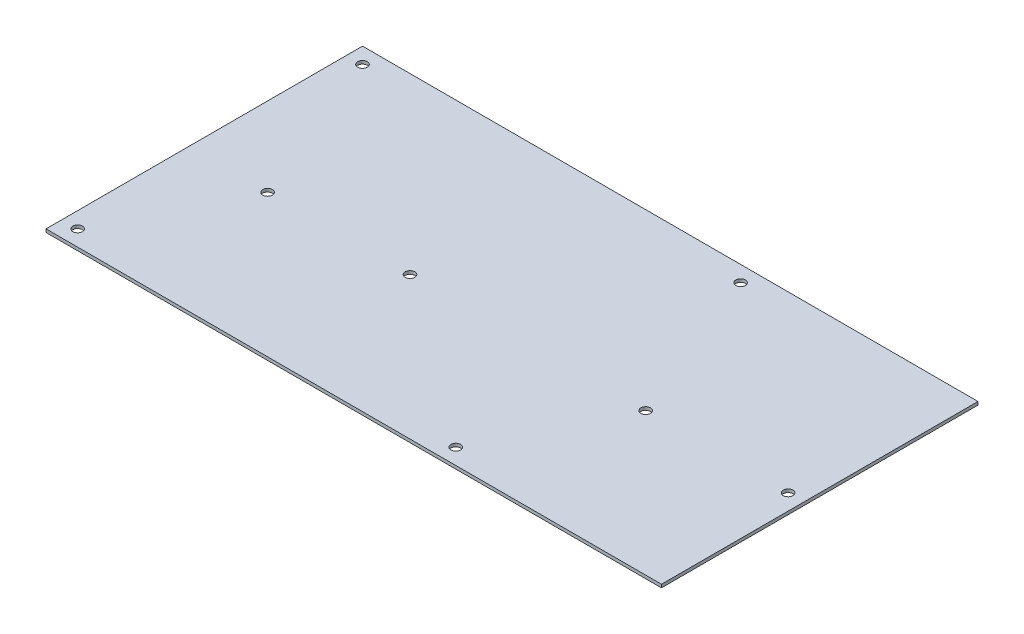
SolidWorks part; units mm, degrees
ref_plane "Front Plane" through (0, 0, 0) normal (0, 0, 1) x (1, 0, 0)
ref_plane "Top Plane" through (0, 0, 0) normal (0, 1, 0) x (1, 0, 0)
ref_plane "Right Plane" through (0, 0, 0) normal (1, 0, 0) x (0, 0, -1)
sketch "Sketch1" plane through (0, 0, 0) normal (0, 1, 0) x (1, 0, 0)
  line L0 (0, 100) -> (75, 100) construction
  line L1 (0, 100) -> (0, 0) construction
  line L2 (0, 0) -> (75, 0) construction
  line L3 (75, 100) -> (75, 0) construction
  line L4 (119.45, 100) -> (194.45, 100) construction
  line L5 (119.45, 100) -> (119.45, 0) construction
  line L6 (119.45, 0) -> (194.45, 0) construction
  line L7 (194.45, 100) -> (194.45, 0) construction
  line L9 (0, 100) -> (194.45, 100)
  line L10 (0, 100) -> (0, 0)
  line L11 (0, 0) -> (194.45, 0)
  line L12 (194.45, 100) -> (194.45, 0)
  circle A0 centre (5, 95) radius 1.524
  circle A1 centre (70, 45) radius 1.524
  circle A2 centre (5, 5) radius 1.524
  circle A3 centre (25, 45) radius 1.524
  circle A4 centre (124.45, 95) radius 1.524
  circle A5 centre (189.45, 45) radius 1.524
  circle A6 centre (124.45, 5) radius 1.524
  circle A7 centre (144.45, 45) radius 1.524
  dimension "D3" = 3.048
  dimension "D6" = 3.048
  dimension "D8" = 3.048
  dimension "D9" = 3.048
  dimension "D16" = 3.048
  dimension "D19" = 3.048
  dimension "D21" = 3.048
  dimension "D22" = 3.048
  dimension "D1" = 75
  dimension "D2" = 100
  dimension "D4" = 5
  dimension "D5" = 5
  dimension "D7" = 5
  dimension "D10" = 55
  dimension "D11" = 45
  dimension "D12" = 5
  dimension "D13" = 5
  dimension "D14" = 75
  dimension "D15" = 100
  dimension "D17" = 5
  dimension "D18" = 5
  dimension "D20" = 5
  dimension "D23" = 55
  dimension "D24" = 45
  dimension "D25" = 5
  dimension "D26" = 5
  dimension "D27" = 44.45
extrude "Boss-Extrude2" add sketch "Sketch1" along normal blind 1
